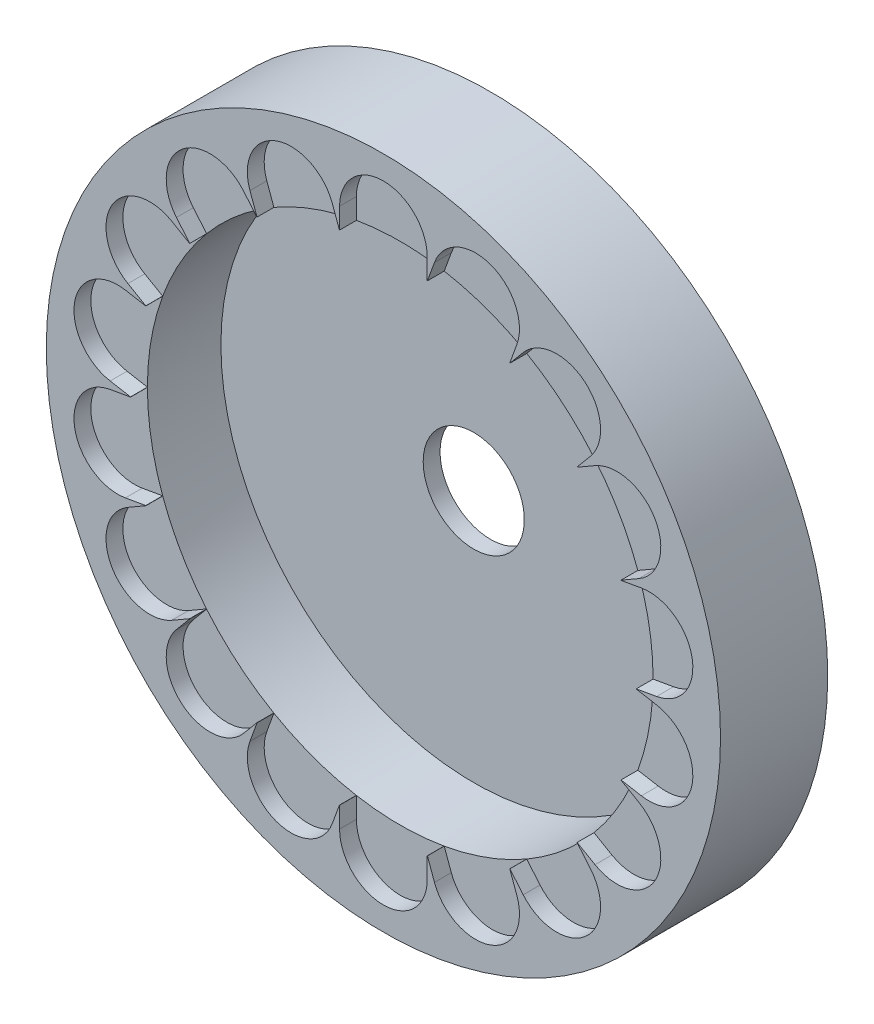
SolidWorks part; units mm, degrees
ref_plane "Front Plane" through (0, 0, 0) normal (0, 0, 1) x (1, 0, 0)
ref_plane "Top Plane" through (0, 0, 0) normal (0, 1, 0) x (1, 0, 0)
ref_plane "Right Plane" through (0, 0, 0) normal (1, 0, 0) x (0, 0, -1)
sketch "Sketch1" plane through (0, 0, 0) normal (0, 0, 1) x (1, 0, 0)
  circle A0 centre (0, 0) radius 63.5
  circle A1 centre (0, 0) radius 47.625
  dimension "D1" = 95.25
  dimension "D2" = 127
extrude "Boss-Extrude1" add sketch "Sketch1" along normal blind 17.018
sketch "Sketch2" plane through (0, 0, 17.018) normal (0, 0, 1) x (1, 0, 0)
  line L0 (0, 50.8) -> (0, -50.8) construction
  line L1 (8.255, 50.8) -> (8.255, -50.8)
  line L2 (-8.255, 50.8) -> (-8.255, -50.8)
  arc A0 (8.255, 50.8) -> (-8.255, 50.8) centre (0, 50.8) ccw
  arc A1 (-8.255, -50.8) -> (8.255, -50.8) centre (0, -50.8) ccw
  point P2 (0, 0)
  dimension "D2" = 8.255
  dimension "D1" = 101.6
extrude "Cut-Extrude1" cut sketch "Sketch2" against normal blind 3.175
pattern_circular "CirPattern1" count 10 every 20 about axis through (0, 0, 0) along (0, 0, 1) of "Cut-Extrude1"
sketch "Sketch3" plane through (0, 0, 0) normal (0, 0, -1) x (-1, 0, 0)
  circle A0 centre (0, 0) radius 63.5
  circle A1 centre (0, 0) radius 9.525
  circle A2 centre (0, 0) radius 63.5 construction
  dimension "D1" = 19.05
extrude "Boss-Extrude2" add sketch "Sketch3" along normal blind 3.175
